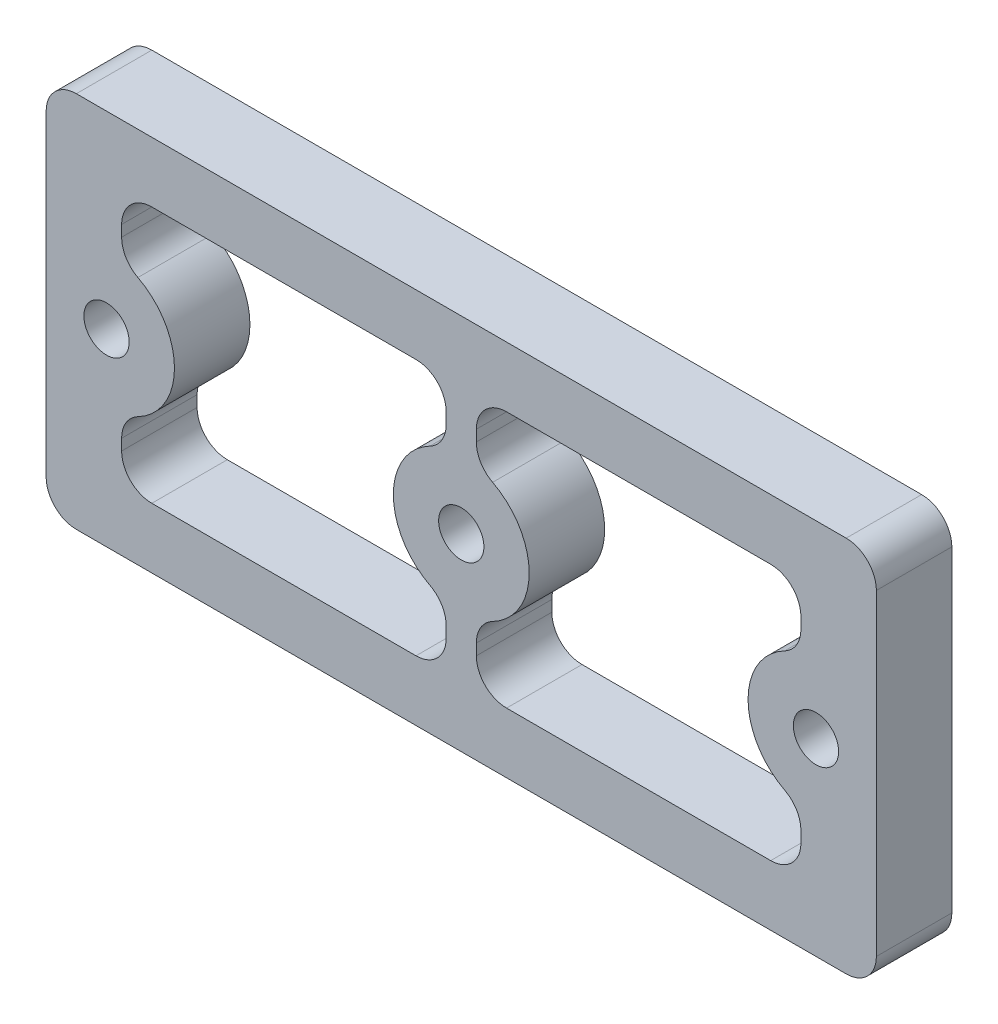
SolidWorks part; units mm, degrees
material "ABS"
ref_plane "前视基准面" through (0, 0, 0) normal (0, 0, 1) x (1, 0, 0)
ref_plane "上视基准面" through (0, 0, 0) normal (0, 1, 0) x (1, 0, 0)
ref_plane "右视基准面" through (0, 0, 0) normal (1, 0, 0) x (0, 0, -1)
sketch "草图1" plane through (0, 0, 0) normal (0, 0, 1) x (1, 0, 0)
  line L1 (-27.5, -12.5) -> (27.5, -12.5)
  line L2 (-27.5, -12.5) -> (-27.5, 12.5)
  line L3 (-27.5, 12.5) -> (27.5, 12.5)
  line L4 (27.5, -12.5) -> (27.5, 12.5)
  line L5 (0, 12.5) -> (0, -12.5) construction
  line L6 (-27.5, 0) -> (27.5, 0) construction
  point P0 (0, 0)
  dimension "D1" = 25
  dimension "D2" = 55
extrude "凸台-拉伸1" add sketch "草图1" along normal blind 5
sketch "草图2" plane through (0, 0, 5) normal (0, 0, 1) x (1, 0, 0)
  line L0 (-23.5, 0) -> (23.5, 0) construction
  line L1 (27.5, -12.5) -> (27.5, 12.5) construction
  circle A0 centre (-23.5, 0) radius 1.5
  circle A1 centre (0, 0) radius 1.5
  circle A2 centre (23.5, 0) radius 1.5
  point P4 (0, 0)
  dimension "D2" = 3
  dimension "D1" = 4
extrude "切除-拉伸1" cut sketch "草图2" against normal blind 5
sketch "草图3" plane through (0, 0, 5) normal (0, 0, 1) x (1, 0, 0)
  line L0 (-27.5, 12.5) -> (-27.5, -12.5) construction
  line L1 (-22.5, -8.5) -> (-1, -8.5)
  line L2 (-22.5, -8.5) -> (-22.5, 8.5)
  line L3 (-22.5, 8.5) -> (-1, 8.5)
  line L4 (-1, -8.5) -> (-1, 8.5)
  line L5 (-11.75, 8.5) -> (-11.75, -8.5) construction
  line L6 (-22.5, 0) -> (-1, 0) construction
  line L7 (-22.5, 0) -> (-1, 0) construction
  line L8 (27.5, 12.5) -> (-27.5, 12.5) construction
  line L9 (-23.5, 0) -> (0, 0) construction
  circle A3 centre (-23.5, 0) radius 4.5
  circle A4 centre (-23.5, 0) radius 4.5
  circle A6 centre (0, 0) radius 4.5
  circle A7 centre (0, 0) radius 4.5
  point P0 (-11.75, 0)
  point P10 (0, 0)
  dimension "D1" = 5
  dimension "D2" = 4
  dimension "D3" = 3
  dimension "D4" = 3
extrude "切除-拉伸2" cut sketch "草图3" against normal blind 5 contours A7 L4 L3 L2 A4 L1
mirror "镜向2" about plane through (0, 0, 0) normal (1, 0, 0) of "切除-拉伸2"
fillet "圆角1" radius 2 16 edges at (1, -4.3875, 2.5) (1, 4.3875, 2.5) (1, 8.5, 2.5) (22.5, 8.5, 2.5) (22.5, 4.3875, 2.5) (22.5, -4.3875, 2.5) (22.5, -8.5, 2.5) (1, -8.5, 2.5) (-22.5, -4.3875, 2.5) (-22.5, 4.3875, 2.5) (-22.5, 8.5, 2.5) (-1, 8.5, 2.5) (-1, 4.3875, 2.5) (-1, -4.3875, 2.5) (-1, -8.5, 2.5) (-22.5, -8.5, 2.5)
fillet "圆角2" radius 2 4 edges at (27.5, -12.5, 2.5) (27.5, 12.5, 2.5) (-27.5, -12.5, 2.5) (-27.5, 12.5, 2.5)
